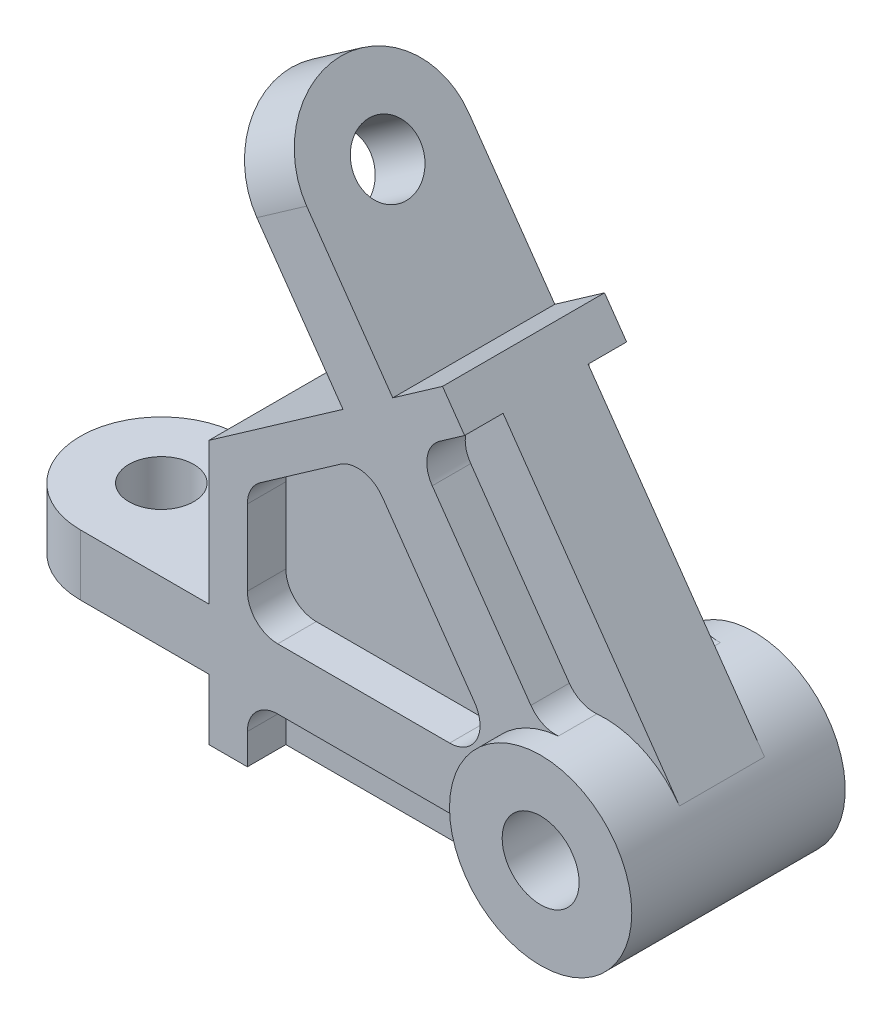
SolidWorks part; units mm, degrees
material "Alliage 1060"
ref_plane "Plan de face" through (0, 0, 0) normal (0, 0, 1) x (1, 0, 0)
ref_plane "Plan de dessus" through (0, 0, 0) normal (0, 1, 0) x (1, 0, 0)
ref_plane "Plan de droite" through (0, 0, 0) normal (1, 0, 0) x (0, 0, -1)
sketch "Esquisse1" plane through (0, 0, 0) normal (0, 0, 1) x (1, 0, 0)
  line L0 (18.4309, 12.9055) -> (-30.5709, 82.8873)
  line L1 (-30.5709, 82.8873) -> (-42.8582, 74.2837)
  line L2 (-42.8582, 74.2837) -> (-75.591, 121.031)
  line L3 (-75.591, 121.031) -> (-87.8783, 112.4273)
  line L4 (-87.8783, 112.4273) -> (-55.1455, 65.68)
  line L5 (-55.1455, 65.68) -> (-88.25, 42.5)
  line L6 (-88.25, 42.5) -> (-88.25, 7.5)
  line L7 (-88.25, 7.5) -> (-140, 7.5)
  line L8 (-140, 7.5) -> (-140, -7.5)
  line L9 (-140, -7.5) -> (-88.25, -7.5)
  line L10 (-88.25, -7.5) -> (-88.25, -22.5605)
  line L11 (-88.25, -22.5605) -> (0.0154, -22.5)
  line L12 (0, 0) -> (-140, 0)
  line L13 (0, 0) -> (-81.7346, 116.7292)
  circle A0 centre (0, 0) radius 22.5
  circle A1 centre (0, 0) radius 9.5
  dimension "D1" = 19
  dimension "D2" = 45
  dimension "D3" = 15
  dimension "D4" = 15
  dimension "D5" = 7.5
  dimension "D6" = 55
  dimension "D7" = 35
  dimension "D8" = 140
  dimension "D9" = 142.5
  dimension "D10" = 0
  dimension "D11" = 0
  dimension "D12" = 51.75
extrude "Boss.-Extru.1" add sketch "Esquisse1" along normal blind 40 contours A0 L0 L1 L2 L3 L13 | A0 L13 L3 L4 L5 L6 L7 L8 L12 | A0 L12 L8 L9 L10 L11 | A1 L12 A0 L13 | A1 L13 A0 L12
sketch "Esquisse2" plane through (6.1436, 4.3018, 0) normal (0.8192, 0.5736, 0) x (0, 0, -1)
  line L0 (-40, 142.5) -> (0, 142.5) construction
  line L1 (0, 85.4321) -> (0, 142.5) construction
  line L6 (0, 85.4321) -> (0, 142.5)
  line L7 (0, 142.5) -> (-40, 142.5)
  line L8 (-40, 142.5) -> (-40, 85.4321)
  line L9 (-40, 85.4321) -> (0, 85.4321)
  line L10 (0, 85.4321) -> (0, 142.5)
  line L11 (0, 142.5) -> (-40, 142.5)
  line L12 (-40, 142.5) -> (-40, 85.4321)
  line L13 (-40, 85.4321) -> (0, 85.4321)
  circle A0 centre (-20, 122.5) radius 8
  circle A1 centre (-20, 122.5) radius 20
  line M8 (0, 142.5) -> (-40, 142.5)
  line M9 (-40, 142.5) -> (-40, 85.4321)
  dimension "D1" = 16
  dimension "D2" = 40
  dimension "D3" = 0
extrude "Enlèv. mat.-Extru.1" cut sketch "Esquisse2" against normal through all contours A0 | A1 L11 M9 | A1 L10 M8
sketch "Esquisse3" plane through (0, 7.5, 0) normal (0, 1, 0) x (1, 0, 0)
  line L0 (-140, -40) -> (-140, 0) construction
  line L1 (-88.25, 0) -> (-140, 0) construction
  line L6 (-88.25, 0) -> (-140, 0)
  line L7 (-140, 0) -> (-140, -40)
  line L8 (-140, -40) -> (-88.25, -40)
  line L9 (-88.25, -40) -> (-88.25, 0)
  line L10 (-88.25, 0) -> (-140, 0)
  line L11 (-140, 0) -> (-140, -40)
  line L12 (-140, -40) -> (-88.25, -40)
  line L13 (-88.25, -40) -> (-88.25, 0)
  circle A0 centre (-120, -20) radius 8
  circle A1 centre (-120, -20) radius 20
  line M8 (-140, 0) -> (-140, -40)
  line M9 (-140, -40) -> (-88.25, -40)
  dimension "D1" = 40
  dimension "D2" = 16
  dimension "D3" = 0
extrude "Enlèv. mat.-Extru.2" cut sketch "Esquisse3" against normal through all contours A1 L10 M8 | A1 L11 M9 | A0
sketch "Esquisse4" plane through (0, 0, 40) normal (0, 0, 1) x (1, 0, 0)
  line L0 (18.4309, 12.9055) -> (-30.5709, 82.8873) construction
  line L1 (-30.5709, 82.8873) -> (-42.8582, 74.2837) construction
  line L2 (-42.8582, 74.2837) -> (-75.591, 121.031) construction
  line L3 (-75.591, 121.031) -> (-87.8783, 112.4273) construction
  line L4 (-87.8783, 112.4273) -> (-55.1455, 65.68) construction
  line L5 (-55.1455, 65.68) -> (-88.25, 42.5) construction
  line L6 (-88.25, 42.5) -> (-88.25, 7.5) construction
  line L7 (-88.25, 7.5) -> (-140, 7.5) construction
  line L8 (-140, 7.5) -> (-140, -7.5) construction
  line L9 (-140, -7.5) -> (-88.25, -7.5) construction
  line L10 (-88.25, -7.5) -> (-88.25, -22.5605) construction
  line L11 (-88.25, -22.5605) -> (0.0154, -22.5) construction
  line L12 (0, 0) -> (-140, 0) construction
  line L13 (0, 0) -> (-81.7346, 116.7292) construction
  line L14 (18.4309, 12.9055) -> (-30.5709, 82.8873)
  line L15 (-30.5709, 82.8873) -> (-42.8582, 74.2837)
  line L16 (-42.8582, 74.2837) -> (-75.591, 121.031)
  line L17 (-75.591, 121.031) -> (-87.8783, 112.4273)
  line L18 (-87.8783, 112.4273) -> (-55.1455, 65.68)
  line L19 (-55.1455, 65.68) -> (-88.25, 42.5)
  line L20 (-88.25, 42.5) -> (-88.25, 7.5)
  line L21 (-88.25, 7.5) -> (-140, 7.5)
  line L22 (-140, 7.5) -> (-140, -7.5)
  line L23 (-140, -7.5) -> (-88.25, -7.5)
  line L24 (-88.25, -7.5) -> (-88.25, -22.5605)
  line L25 (-88.25, -22.5605) -> (0.0154, -22.5)
  line L26 (0, 0) -> (-140, 0)
  line L27 (0, 0) -> (-81.7346, 116.7292)
  circle A1 centre (0, 0) radius 22.5
  circle A2 centre (0, 0) radius 22.5
  circle A3 centre (0, 0) radius 9.5
  circle A4 centre (0, 0) radius 9.5
  arc M7 (0.0154, -22.5) -> (18.4309, 12.9055) centre (0, 0) ccw
  circle M16 centre (0, 0) radius 9.5
  dimension "D1" = 0
  dimension "D2" = 0
extrude "Boss.-Extru.2" add sketch "Esquisse4" along normal blind 6.35 contours A2 L27 L26 M7 M16 | L27 A2 L26 M16
sketch "Esquisse5" plane through (0, 0, 0) normal (0, 0, -1) x (-1, 0, 0)
  line L0 (-18.4309, 12.9055) -> (30.5709, 82.8873) construction
  line L1 (30.5709, 82.8873) -> (42.8582, 74.2837) construction
  line L2 (42.8582, 74.2837) -> (75.591, 121.031) construction
  line L3 (75.591, 121.031) -> (87.8783, 112.4273) construction
  line L4 (87.8783, 112.4273) -> (55.1455, 65.68) construction
  line L5 (55.1455, 65.68) -> (88.25, 42.5) construction
  line L6 (88.25, 42.5) -> (88.25, 7.5) construction
  line L7 (88.25, 7.5) -> (140, 7.5) construction
  line L8 (140, 7.5) -> (140, -7.5) construction
  line L9 (140, -7.5) -> (88.25, -7.5) construction
  line L10 (88.25, -7.5) -> (88.25, -22.5605) construction
  line L11 (88.25, -22.5605) -> (-0.0154, -22.5) construction
  line L12 (0, 0) -> (140, 0) construction
  line L13 (0, 0) -> (81.7346, 116.7292) construction
  line L14 (-18.4309, 12.9055) -> (30.5709, 82.8873)
  line L15 (30.5709, 82.8873) -> (42.8582, 74.2837)
  line L16 (42.8582, 74.2837) -> (75.591, 121.031)
  line L17 (75.591, 121.031) -> (87.8783, 112.4273)
  line L18 (87.8783, 112.4273) -> (55.1455, 65.68)
  line L19 (55.1455, 65.68) -> (88.25, 42.5)
  line L20 (88.25, 42.5) -> (88.25, 7.5)
  line L21 (88.25, 7.5) -> (140, 7.5)
  line L22 (140, 7.5) -> (140, -7.5)
  line L23 (140, -7.5) -> (88.25, -7.5)
  line L24 (88.25, -7.5) -> (88.25, -22.5605)
  line L25 (88.25, -22.5605) -> (-0.0154, -22.5)
  line L26 (0, 0) -> (140, 0)
  line L27 (0, 0) -> (81.7346, 116.7292)
  circle A1 centre (0, 0) radius 22.5
  circle A2 centre (0, 0) radius 22.5
  circle A3 centre (0, 0) radius 9.5
  circle A4 centre (0, 0) radius 9.5
  arc M13 (-18.4309, 12.9055) -> (-0.0154, -22.5) centre (0, 0) ccw
  circle M16 centre (0, 0) radius 9.5
  dimension "D1" = 0
  dimension "D2" = 0
extrude "Boss.-Extru.3" add sketch "Esquisse5" along normal blind 6.35 contours L26 A2 L27 M16 | L27 A2 L26 M13 M16
sketch "Esquisse6" plane through (0, 0, 40) normal (0, 0, 1) x (1, 0, 0)
  line L0 (-25.1219, 75.1054) -> (-31.2656, 70.8036)
  line L1 (18.4309, 12.9055) -> (-30.5709, 82.8873) construction
  line L2 (-33.1074, 60.3581) -> (-8.7583, 25.584)
  line L3 (-88.25, -22.5605) -> (0.0154, -22.5) construction
  line L4 (-30.5709, 82.8873) -> (-42.8582, 74.2837) construction
  line L5 (-42.8582, 74.2837) -> (-64.1195, 104.6479) construction
  line L6 (-64.1195, 104.6479) -> (-76.4068, 96.0443) construction
  line L7 (-76.4068, 96.0443) -> (-55.1455, 65.68) construction
  line L8 (-55.1455, 65.68) -> (-88.25, 42.5) construction
  line L9 (-88.25, 42.5) -> (-88.25, 7.5) construction
  line L10 (-88.25, 7.5) -> (-120, 7.5) construction
  line L11 (-120, 7.5) -> (-120, -7.5) construction
  line L12 (-120, -7.5) -> (-88.25, -7.5) construction
  line L13 (-88.25, -7.5) -> (-88.25, -22.5605) construction
  line L14 (-88.25, -22.5605) -> (0.0154, -22.5)
  line L15 (18.4309, 12.9055) -> (-30.5709, 82.8873)
  line L16 (-30.5709, 82.8873) -> (-42.8582, 74.2837)
  line L17 (-42.8582, 74.2837) -> (-64.1195, 104.6479)
  line L18 (-64.1195, 104.6479) -> (-76.4068, 96.0443)
  line L19 (-76.4068, 96.0443) -> (-55.1455, 65.68)
  line L20 (-55.1455, 65.68) -> (-88.25, 42.5)
  line L21 (-88.25, 42.5) -> (-88.25, 7.5)
  line L22 (-88.25, 7.5) -> (-120, 7.5)
  line L23 (-120, 7.5) -> (-120, -7.5)
  line L24 (-120, -7.5) -> (-88.25, -7.5)
  line L25 (-88.25, -7.5) -> (-88.25, -22.5605)
  line L26 (-45.3947, 51.7545) -> (-22.6711, 19.3018)
  line L27 (-28.8147, 7.5) -> (-71.25, 7.5)
  line L28 (-78.75, 15) -> (-78.75, 33.6504)
  line L29 (-75.5518, 39.794) -> (-55.8401, 53.5963)
  line L30 (-78.75, -22.554) -> (-78.75, -15)
  line L31 (-71.25, -7.5) -> (-25.9808, -7.5)
  line L32 (0, 0) -> (-120, 0)
  line L33 (0, 0) -> (-70.2631, 100.3461)
  arc A0 (-31.2656, 70.8036) -> (-33.1074, 60.3581) centre (-26.9637, 64.6599) ccw
  circle A1 centre (0, 0) radius 22.5 construction
  arc A2 (18.4309, 12.9055) -> (0.0154, -22.5) centre (0, 0) ccw construction
  arc A3 (-19.4856, -11.25) -> (-1.961, 22.4144) centre (0, 0) ccw
  arc A4 (18.4309, 12.9055) -> (-6.0238, 21.6787) centre (0, 0) ccw
  arc A5 (-22.6711, 19.3018) -> (-28.8147, 7.5) centre (-28.8147, 15) cw
  arc A6 (-45.3947, 51.7545) -> (-55.8401, 53.5963) centre (-51.5383, 47.4526) ccw
  arc A7 (-71.25, 7.5) -> (-78.75, 15) centre (-71.25, 15) cw
  arc A8 (-78.75, 33.6504) -> (-75.5518, 39.794) centre (-71.25, 33.6504) cw
  arc A9 (-78.75, -15) -> (-71.25, -7.5) centre (-71.25, -15) cw
  arc A10 (-12.9055, 18.4309) -> (-22.5, 0) centre (0, 0) ccw
  arc A11 (-12.9055, 18.4309) -> (-22.5, 0) centre (0, 0) ccw
  arc A12 (-21.2132, -7.5) -> (0.0154, -22.5) centre (0, 0) ccw
  arc A13 (-8.7583, 25.584) -> (-1.961, 22.4144) centre (-2.6147, 29.8858) ccw
  arc A14 (-25.9808, -7.5) -> (-19.4856, -11.25) centre (-25.9808, -15) cw
  arc M30 (0.0154, -22.5) -> (18.4309, 12.9055) centre (0, 0) cw
  line M31 (18.4309, 12.9055) -> (-30.5709, 82.8873)
  dimension "D5" = 7.5
  dimension "D1" = 7.5
  dimension "D2" = 7.5
  dimension "D10" = 7.5
  dimension "D13" = 7.5
  dimension "D3" = 9.5
  dimension "D4" = 9.5
  dimension "D6" = 9.5
  dimension "D7" = 7.5
  dimension "D8" = 7.5
  dimension "D9" = 7.5
  dimension "D11" = 7.5
  dimension "D12" = 9.5
extrude "Enlèv. mat.-Extru.3" cut sketch "Esquisse6" against normal blind 9.5 contours A8 L28 A7 L27 A5 L26 A6 L29 | L0 A0 L2 M30 M31 | A9 L30 L14 L31 M30
sketch "Esquisse7" plane through (0, 0, 0) normal (0, 0, -1) x (-1, 0, 0)
  line L0 (25.9808, -7.5) -> (71.25, -7.5) construction
  line L1 (78.75, -15) -> (78.75, -22.554) construction
  line L2 (78.75, -22.554) -> (-0.0154, -22.5) construction
  line L3 (33.1074, 60.3581) -> (8.7583, 25.584) construction
  line L4 (-18.4309, 12.9055) -> (25.1219, 75.1054) construction
  line L5 (25.1219, 75.1054) -> (31.2656, 70.8036) construction
  line L6 (78.75, 33.6504) -> (78.75, 15) construction
  line L7 (71.25, 7.5) -> (28.8147, 7.5) construction
  line L8 (22.6711, 19.3018) -> (45.3947, 51.7545) construction
  line L9 (55.8401, 53.5963) -> (75.5518, 39.794) construction
  line L10 (25.9808, -7.5) -> (71.25, -7.5)
  line L11 (78.75, -15) -> (78.75, -22.554)
  line L12 (78.75, -22.554) -> (-0.0154, -22.5)
  line L13 (33.1074, 60.3581) -> (8.7583, 25.584)
  line L14 (-18.4309, 12.9055) -> (25.1219, 75.1054)
  line L15 (25.1219, 75.1054) -> (31.2656, 70.8036)
  line L16 (78.75, 33.6504) -> (78.75, 15)
  line L17 (71.25, 7.5) -> (28.8147, 7.5)
  line L18 (22.6711, 19.3018) -> (45.3947, 51.7545)
  line L19 (55.8401, 53.5963) -> (75.5518, 39.794)
  arc A2 (25.9808, -7.5) -> (19.4856, -11.25) centre (25.9808, -15) ccw construction
  arc A3 (78.75, -15) -> (71.25, -7.5) centre (71.25, -15) ccw construction
  arc A4 (-0.0154, -22.5) -> (19.4856, -11.25) centre (0, 0) ccw construction
  arc A5 (1.961, 22.4144) -> (8.7583, 25.584) centre (2.6147, 29.8858) ccw construction
  arc A6 (1.961, 22.4144) -> (-18.4309, 12.9055) centre (0, 0) ccw construction
  arc A7 (33.1074, 60.3581) -> (31.2656, 70.8036) centre (26.9637, 64.6599) ccw construction
  arc A8 (78.75, 33.6504) -> (75.5518, 39.794) centre (71.25, 33.6504) ccw construction
  arc A9 (71.25, 7.5) -> (78.75, 15) centre (71.25, 15) ccw construction
  arc A10 (22.6711, 19.3018) -> (28.8147, 7.5) centre (28.8147, 15) ccw construction
  arc A11 (55.8401, 53.5963) -> (45.3947, 51.7545) centre (51.5383, 47.4526) ccw construction
  arc A12 (25.9808, -7.5) -> (19.4856, -11.25) centre (25.9808, -15) ccw
  arc A13 (78.75, -15) -> (71.25, -7.5) centre (71.25, -15) ccw
  arc A14 (-0.0154, -22.5) -> (19.4856, -11.25) centre (0, 0) ccw
  arc A15 (1.961, 22.4144) -> (8.7583, 25.584) centre (2.6147, 29.8858) ccw
  arc A16 (1.961, 22.4144) -> (-18.4309, 12.9055) centre (0, 0) ccw
  arc A17 (33.1074, 60.3581) -> (31.2656, 70.8036) centre (26.9637, 64.6599) ccw
  arc A18 (78.75, 33.6504) -> (75.5518, 39.794) centre (71.25, 33.6504) ccw
  arc A19 (71.25, 7.5) -> (78.75, 15) centre (71.25, 15) ccw
  arc A20 (22.6711, 19.3018) -> (28.8147, 7.5) centre (28.8147, 15) ccw
  arc A21 (55.8401, 53.5963) -> (45.3947, 51.7545) centre (51.5383, 47.4526) ccw
extrude "Enlèv. mat.-Extru.4" cut sketch "Esquisse7" against normal blind 9.5
equation "\"A\"= 122.5"
equation "\"B\"= 15"
equation "\"C\"= 55"
equation "\"D3@Esquisse1\"=\"B\""
equation "\"D8@Esquisse6\"=\"B\"/2"
equation "\"D4@Esquisse1\"=\"B\""
equation "\"D5@Esquisse1\"=\"B\"/2"
equation "\"D9@Esquisse1\"=\"A\"+20"
equation "\"D6@Esquisse1\"=\"C\""
